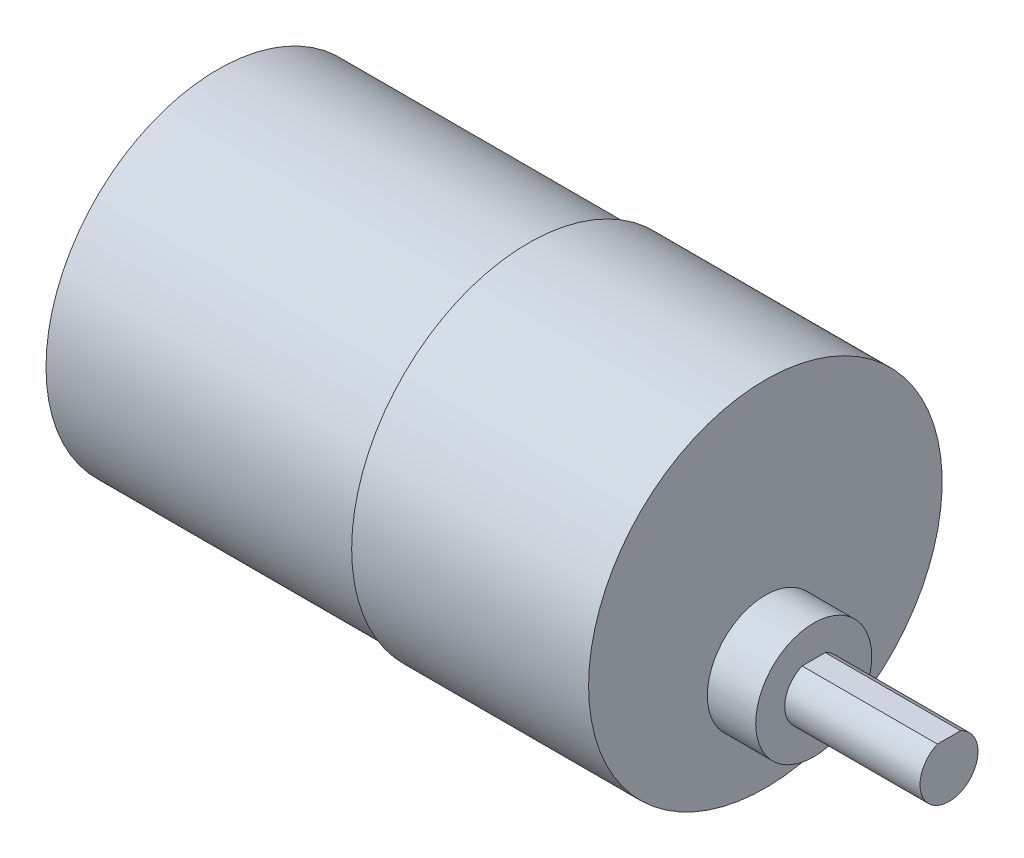
SolidWorks part; units mm, degrees
ref_plane "Front Plane" through (0, 0, 0) normal (0, 0, 1) x (1, 0, 0)
ref_plane "Top Plane" through (0, 0, 0) normal (0, 1, 0) x (1, 0, 0)
ref_plane "Right Plane" through (0, 0, 0) normal (1, 0, 0) x (0, 0, -1)
sketch "Sketch1" plane through (0, 0, 0) normal (0, 0, 1) x (1, 0, 0)
  line L0 (28.321, 18.288) -> (3.808, 18.288)
  line L1 (3.808, -18.288) -> (28.321, -18.288)
  line L2 (-28.321, -17.78) -> (-28.321, 17.78)
  line L3 (3.808, 18.288) -> (28.321, 18.288)
  line L4 (28.321, -18.288) -> (28.321, 18.288)
  line L5 (-37.4495, 0) -> (42.329, 0) construction
  line L7 (3.808, 17.78) -> (-28.321, 17.78)
  line L8 (3.808, 18.288) -> (3.808, 17.78)
  line L10 (3.808, -17.78) -> (-28.321, -17.78)
  line L11 (3.808, -18.288) -> (3.808, -17.78)
  dimension "D1" = 36.576
  dimension "D2" = 56.642
revolve "Revolve1" add sketch "Sketch1" angle 360 about L5
sketch "Sketch2" plane through (28.321, 0, 0) normal (1, 0, 0) x (0, 0, -1)
  line L0 (0, 0) -> (0, -7.0002)
  circle A0 centre (0, -7.0002) radius 6
extrude "Boss-Extrude1" add sketch "Sketch2" along normal blind 5
sketch "Sketch3" plane through (33.321, 0, 0) normal (1, 0, 0) x (0, 0, -1)
  line L1 (-1.199, -4.2502) -> (1.199, -4.2502)
  arc A0 (-1.199, -4.2502) -> (1.199, -4.2502) centre (0, -7.0002) ccw
extrude "Boss-Extrude2" add sketch "Sketch3" along normal blind 14
